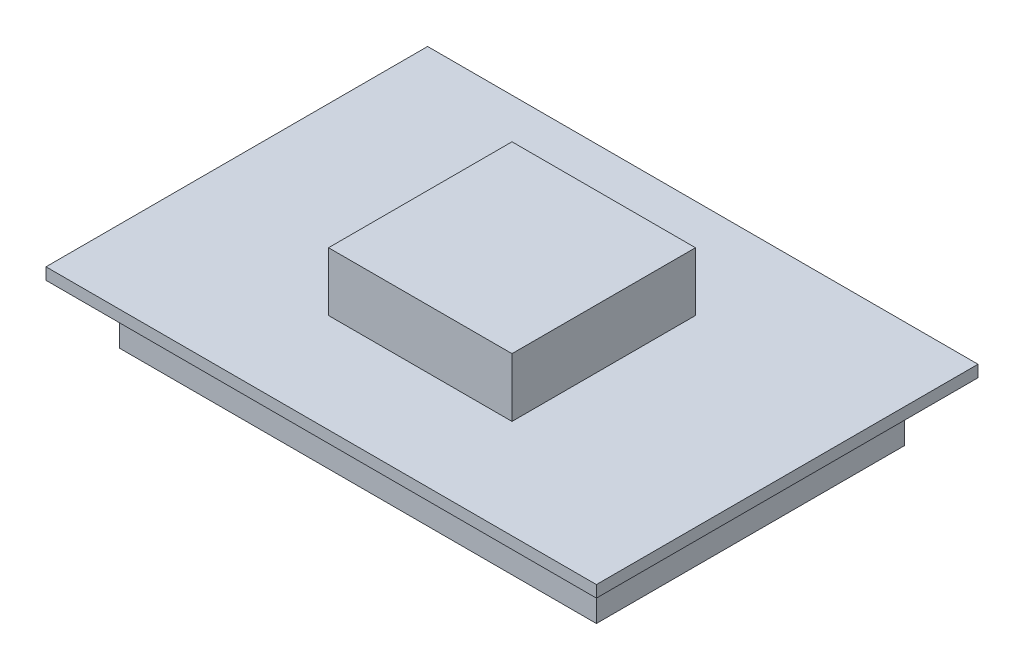
SolidWorks part; units mm, degrees
ref_plane "Front Plane" through (0, 0, 0) normal (0, 0, 1) x (1, 0, 0)
ref_plane "Top Plane" through (0, 0, 0) normal (0, 1, 0) x (1, 0, 0)
ref_plane "Right Plane" through (0, 0, 0) normal (1, 0, 0) x (0, 0, -1)
ref_plane "PZm14" through (0, -14, 0) normal (0, 1, 0) x (1, 0, 0)
sketch "Sketch1" plane through (0, -14, 0) normal (0, 1, 0) x (1, 0, 0)
  line L0 (-46, -149) -> (29, -149)
  line L1 (29, -149) -> (29, -97)
  line L2 (29, -97) -> (-46, -97)
  line L3 (-46, -97) -> (-46, -149)
extrude "ESP32 PCB" add sketch "Sketch1" along normal blind 1.6
ref_plane "PZm12_4" through (0, -12.4, 0) normal (0, 1, 0) x (1, 0, 0)
sketch "Sketch2" plane through (0, -12.4, 0) normal (0, 1, 0) x (1, 0, 0)
  line L0 (-21, -135.5) -> (4, -135.5)
  line L1 (4, -135.5) -> (4, -110.5)
  line L2 (4, -110.5) -> (-21, -110.5)
  line L3 (-21, -110.5) -> (-21, -135.5)
extrude "GNSS Patch" add sketch "Sketch2" along normal blind 8
ref_plane "PZm22" through (0, -22, 0) normal (0, 1, 0) x (1, 0, 0)
sketch "Sketch3" plane through (0, -22, 0) normal (0, 1, 0) x (1, 0, 0)
  line L0 (-41, -144) -> (24, -144)
  line L1 (24, -144) -> (24, -102)
  line L2 (24, -102) -> (-41, -102)
  line L3 (-41, -102) -> (-41, -144)
extrude "LiPo" add sketch "Sketch3" along normal blind 8
